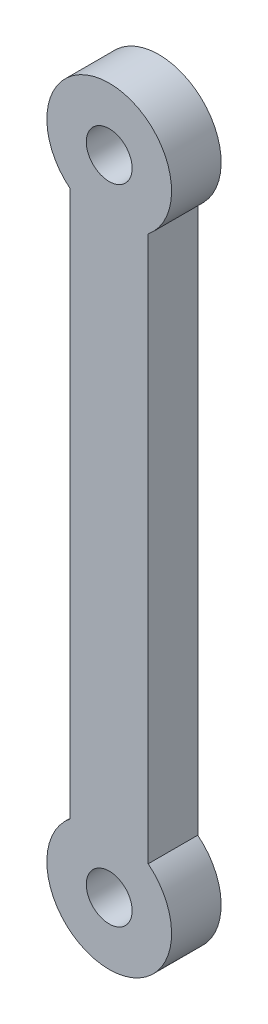
SolidWorks part; units mm, degrees
ref_plane "Front Plane" through (0, 0, 0) normal (0, 0, 1) x (1, 0, 0)
ref_plane "Top Plane" through (0, 0, 0) normal (0, 1, 0) x (1, 0, 0)
ref_plane "Right Plane" through (0, 0, 0) normal (1, 0, 0) x (0, 0, -1)
sketch "Sketch1" plane through (0, 0, 0) normal (0, 0, 1) x (1, 0, 0)
  line L0 (0, 0) -> (0, 59.5848) construction
  line L1 (-2.5, 3.1225) -> (-2.5, 38.1225)
  line L2 (2.5, 3.1225) -> (2.5, 38.1225)
  line L6 (-18.6194, -3.784) -> (-46.0751, -8.5935) construction
  arc A0 (-2.5, 3.1225) -> (-3.3802, 2.1387) centre (0, 0) ccw
  arc A1 (2.5, 38.1225) -> (-2.5, 38.1225) centre (0, 41.245) ccw
  arc A3 (-2.5621, -3.0718) -> (2.5, 3.1225) centre (0, 0) ccw
  arc A5 (-3.3802, 2.1387) -> (-2.5621, -3.0718) centre (0, 0) ccw
  dimension "D2" = 8
  dimension "D4" = 8
  dimension "D1" = 5
  dimension "D3" = 35
extrude "Boss-Extrude1" add sketch "Sketch1" along normal blind 3.18
sketch "Sketch2" plane through (0, 0, 3.18) normal (0, 0, 1) x (1, 0, 0)
  circle A0 centre (0, 41.245) radius 1.47
  circle A1 centre (0, 0) radius 1.47
  dimension "D1" = 2.94
  dimension "D2" = 2.94
extrude "Cut-Extrude1" cut sketch "Sketch2" against normal through all
